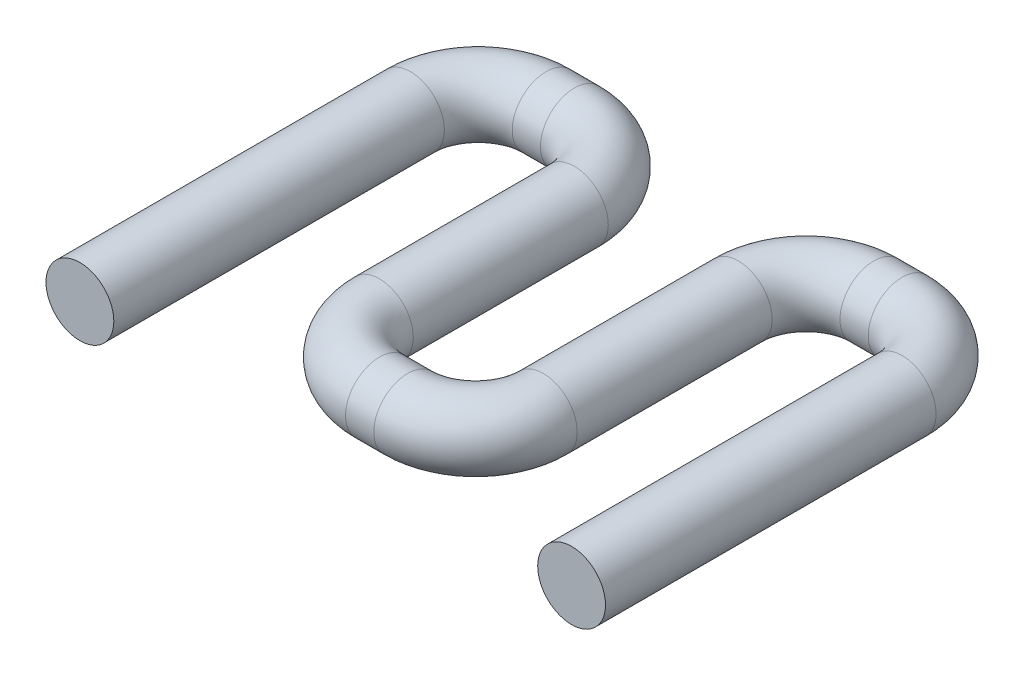
SolidWorks part; units mm, degrees
ref_plane "Front Plane" through (0, 0, 0) normal (0, 0, 1) x (1, 0, 0)
ref_plane "Top Plane" through (0, 0, 0) normal (0, 1, 0) x (1, 0, 0)
ref_plane "Right Plane" through (0, 0, 0) normal (1, 0, 0) x (0, 0, -1)
sketch "Sketch6" [suppressed] plane through (0, 0, 0) normal (0, 0, 1) x (1, 0, 0)
  line L1 (22.225, -9.525) -> (-22.225, -9.525)
  line L2 (22.225, -9.525) -> (22.225, -12.7)
  line L3 (22.225, -12.7) -> (-22.225, -12.7)
  line L4 (-22.225, -9.525) -> (-22.225, -12.7)
  line L5 (22.225, -9.525) -> (-22.225, -12.7) construction
  line L6 (22.225, -12.7) -> (-22.225, -9.525) construction
  point P0 (0, -11.1125)
  dimension "D1" = 44.45
  dimension "D2" = 3.175
  dimension "D3" = 12.7
sketch "Sketch1" plane through (0, 0, 0) normal (0, 1, 0) x (1, 0, 0)
  line L0 (0, 0) -> (0, 123.825)
  line L1 (25.4, 149.225) -> (35.9918, 149.225)
  line L2 (61.3918, 123.825) -> (61.3918, 50.8)
  line L3 (86.7918, 25.4) -> (97.3836, 25.4)
  line L4 (122.7836, 50.8) -> (122.7836, 123.825)
  line L5 (148.1836, 149.225) -> (158.7754, 149.225)
  line L6 (184.1754, 123.825) -> (184.1754, 0)
  arc A0 (86.7918, 25.4) -> (61.3918, 50.8) centre (86.7918, 50.8) cw
  arc A1 (61.3918, 123.825) -> (35.9918, 149.225) centre (35.9918, 123.825) ccw
  arc A2 (25.4, 149.225) -> (0, 123.825) centre (25.4, 123.825) ccw
  arc A3 (184.1754, 123.825) -> (158.7754, 149.225) centre (158.7754, 123.825) ccw
  arc A4 (148.1836, 149.225) -> (122.7836, 123.825) centre (148.1836, 123.825) ccw
  arc A5 (122.7836, 50.8) -> (97.3836, 25.4) centre (97.3836, 50.8) cw
  point P12 (0, 149.225)
  dimension "D2" = 25.4
  dimension "D3" = 61.3918
  dimension "D4" = 25.4
  dimension "D1" = 149.225
sweep "Sweep1" add path "Sketch1" circular profile diameter 25.4 parameters "D3"=25.4
